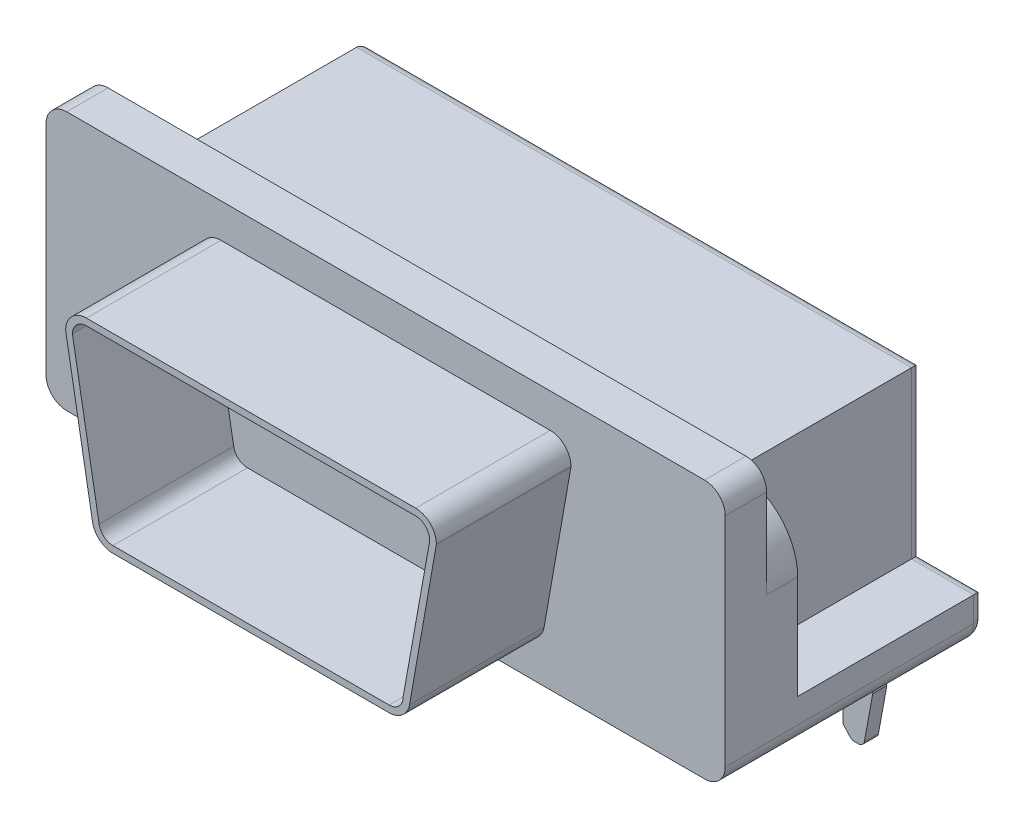
SolidWorks part; units mm, degrees
ref_plane "Front Plane" through (0, 0, 0) normal (0, 0, 1) x (1, 0, 0)
ref_plane "Top Plane" through (0, 0, 0) normal (0, 1, 0) x (1, 0, 0)
ref_plane "Right Plane" through (0, 0, 0) normal (1, 0, 0) x (0, 0, -1)
sketch "Sketch1" plane through (0, 0, 0) normal (0, 1, 0) x (1, 0, 0)
  line L0 (-9.7129, 0) -> (15.2771, 0) construction
  line L13 (-6.925, 1.42) -> (3.5677, 1.42) construction
  line L14 (-5.54, -1.42) -> (3.3918, -1.42) construction
  line L15 (1.045, -1.76) -> (1.045, -1.08)
  line L16 (3.5677, 1.42) -> (3.5677, -3.2608) construction
  line L17 (-5.54, -1.42) -> (-5.54, 1.42) construction
  line L18 (0, 0) -> (0, 1.42) construction
  line L19 (0, 1.42) -> (0, -1.42) construction
  line L20 (-2.77, -1.42) -> (-2.77, 1.42) construction
  line L21 (-1.725, -1.76) -> (-1.045, -1.76)
  line L26 (-1.725, -1.76) -> (-1.725, -1.08)
  line L27 (-1.725, -1.08) -> (-1.045, -1.08)
  line L28 (-5.88, 1.76) -> (-5.2, 1.76)
  line L29 (-5.88, 1.76) -> (-5.88, 1.08)
  line L30 (-5.88, 1.08) -> (-5.2, 1.08)
  line L31 (-5.2, 1.76) -> (-5.2, 1.08)
  line L32 (-5.88, 1.76) -> (-5.2, 1.08) construction
  line L33 (-5.88, 1.08) -> (-5.2, 1.76) construction
  line L34 (-3.11, 1.76) -> (-2.43, 1.76)
  line L35 (-3.11, 1.76) -> (-3.11, 1.08)
  line L36 (-3.11, 1.08) -> (-2.43, 1.08)
  line L37 (-2.43, 1.76) -> (-2.43, 1.08)
  line L38 (-3.11, 1.76) -> (-2.43, 1.08) construction
  line L39 (-3.11, 1.08) -> (-2.43, 1.76) construction
  line L44 (-1.045, -1.76) -> (-1.045, -1.08)
  line L45 (-1.725, -1.76) -> (-1.045, -1.08) construction
  line L50 (-1.725, -1.08) -> (-1.045, -1.76) construction
  line L51 (-4.495, -1.76) -> (-3.815, -1.76)
  line L52 (-0.34, 1.76) -> (0.34, 1.76)
  line L53 (-0.34, 1.76) -> (-0.34, 1.08)
  line L54 (-0.34, 1.08) -> (0.34, 1.08)
  line L55 (0.34, 1.76) -> (0.34, 1.08)
  line L56 (-0.34, 1.76) -> (0.34, 1.08) construction
  line L57 (-0.34, 1.08) -> (0.34, 1.76) construction
  line L62 (-4.495, -1.76) -> (-4.495, -1.08)
  line L63 (-4.495, -1.08) -> (-3.815, -1.08)
  line L64 (-3.815, -1.76) -> (-3.815, -1.08)
  line L65 (-4.495, -1.76) -> (-3.815, -1.08) construction
  line L66 (-4.495, -1.08) -> (-3.815, -1.76) construction
  line L67 (1.725, -1.08) -> (1.045, -1.08)
  line L68 (1.725, -1.76) -> (1.725, -1.08)
  line L69 (1.725, -1.76) -> (1.045, -1.76)
  line L70 (4.495, -1.76) -> (4.495, -1.08)
  line L71 (4.495, -1.76) -> (3.815, -1.76)
  line L72 (3.815, -1.76) -> (3.815, -1.08)
  line L73 (4.495, -1.08) -> (3.815, -1.08)
  line L74 (5.88, 1.76) -> (5.88, 1.08)
  line L75 (5.88, 1.76) -> (5.2, 1.76)
  line L76 (5.2, 1.76) -> (5.2, 1.08)
  line L77 (5.88, 1.08) -> (5.2, 1.08)
  line L78 (3.11, 1.08) -> (2.43, 1.08)
  line L79 (3.11, 1.76) -> (3.11, 1.08)
  line L80 (2.43, 1.76) -> (2.43, 1.08)
  line L81 (3.11, 1.76) -> (2.43, 1.76)
  point P6 (-1.385, -1.42)
  point P23 (-4.155, -1.42)
  dimension "D1" = 2.84
  dimension "D2" = 1.42
  dimension "D3" = 1.385
  dimension "D4" = 2.77
  dimension "D5" = 2.77
  dimension "D6" = 1.385
  dimension "D7" = 0.68
extrude "Boss-Extrude1" add sketch "Sketch1" against normal blind 3.2
sketch "Sketch2" plane through (0, 0, 0) normal (0, 1, 0) x (1, 0, 0)
  line L0 (-5.88, 1.08) -> (-5.2, 1.76) construction
  line L1 (-16.4, -9.52) -> (16.4, -9.52)
  line L2 (-16.4, -9.52) -> (-16.4, 2.98)
  line L3 (-16.4, 2.98) -> (16.4, 2.98)
  line L4 (16.4, -9.52) -> (16.4, 2.98)
  line L5 (-5.2, 1.76) -> (-5.88, 1.76) construction
  line L6 (-5.88, 1.76) -> (-5.179, 1.059) construction
  line L7 (-5.179, 1.059) -> (-5.54, 1.42) construction
  line L8 (0, 0) -> (-7.3423, 0) construction
  line L9 (-4.495, -1.76) -> (-3.815, -1.08) construction
  line L10 (-4.495, -1.08) -> (-3.815, -1.76) construction
  dimension "D1" = 10.94
  dimension "D2" = 12.5
  dimension "D3" = 32.8
  dimension "D4" = 16.4
extrude "Boss-Extrude2" add sketch "Sketch2" along normal blind 12.5
fillet "Fillet1" radius 1 4 edges at (16.4, 12.5, 3.27) (16.4, 0, 3.27) (-16.4, 0, 3.27) (-16.4, 12.5, 3.27)
sketch "Sketch3" plane through (16.4, 0, 0) normal (1, 0, 0) x (0, 0, -1)
  line L1 (2.98, 12.5) -> (-7.52, 12.5)
  line L2 (2.98, 12.5) -> (2.98, 10.2)
  line L3 (2.98, 10.2) -> (-7.52, 10.2)
  line L4 (-7.52, 12.5) -> (-7.52, 10.2)
  dimension "D1" = 2.3
  dimension "D2" = 10.5
extrude "Cut-Extrude1" cut sketch "Sketch3" against normal through all
sketch "Sketch4" plane through (0, 0, 0) normal (0, -1, 0) x (1, 0, 0)
  line L0 (0, 0) -> (-12.495, 0) construction
  line L1 (0, 0) -> (0, 5.4076) construction
  line L2 (-14.345, 0.34) -> (-10.645, 0.34)
  line L3 (-14.345, 0.34) -> (-14.345, -0.34)
  line L4 (-14.345, -0.34) -> (-10.645, -0.34)
  line L5 (-10.645, 0.34) -> (-10.645, -0.34)
  line L6 (-14.345, 0.34) -> (-10.645, -0.34) construction
  line L7 (-14.345, -0.34) -> (-10.645, 0.34) construction
  line L8 (10.645, 0.34) -> (10.645, -0.34)
  line L9 (14.345, -0.34) -> (10.645, -0.34)
  line L10 (14.345, 0.34) -> (14.345, -0.34)
  line L11 (14.345, 0.34) -> (10.645, 0.34)
  dimension "D1" = 12.495
  dimension "D2" = 0.68
  dimension "D3" = 3.7
extrude "Boss-Extrude3" add sketch "Sketch4" along normal blind 4
sketch "Sketch6" plane through (0, 0, 0.34) normal (0, 0, 1) x (1, 0, 0)
  line L0 (-14.345, 0) -> (-10.645, -4) construction
  line L2 (-10.645, 0) -> (-14.345, -4) construction
  line L3 (-12.9071, 0) -> (-12.9071, -3.5332) construction
  line L4 (-10.645, 0) -> (-14.345, 0) construction
  line L5 (-12.9071, -3.5332) -> (-13.3389, -4) construction
  line L6 (-10.645, -4) -> (-14.345, -4) construction
  line L8 (-13.8964, -4) -> (-14.345, -1.5508) construction
  line L9 (-14.345, -4) -> (-14.345, 0) construction
  line L10 (-14.345, -1.5508) -> (-13.8133, -0.7806) construction
  line L11 (-13.8133, -0.7806) -> (-13.8133, 0) construction
  line L12 (-15.4, 0) -> (15.4, 0) construction
  line L15 (-14.345, -1.5508) -> (-13.8133, -0.7806)
  line L16 (-13.8133, -0.7806) -> (-13.8133, 0)
  line L20 (-12.495, -2) -> (-12.495, 0) construction
  line L22 (-14.8273, 0) -> (-14.8273, -4)
  line L23 (-14.8273, -4) -> (-13.8964, -4)
  line L24 (-13.8964, -4) -> (-14.345, -1.5508)
  line L25 (-14.345, 0) -> (-14.8273, 0)
  line L26 (-12.9071, 0) -> (-12.0829, 0)
  line L40 (-13.8133, 0) -> (-14.345, 0)
  line L42 (-12.9071, 0) -> (-12.9071, -3.5332)
  line L43 (-12.9071, -3.5332) -> (-13.3389, -4)
  line L44 (-12.495, -2) -> (-12.495, -4) construction
  line L45 (-13.3389, -4) -> (-11.6511, -4)
  line L46 (-11.1767, -0.7806) -> (-11.1767, 0) construction
  line L47 (-10.645, -1.5508) -> (-11.1767, -0.7806) construction
  line L48 (-11.0936, -4) -> (-10.645, -1.5508) construction
  line L49 (-12.0829, -3.5332) -> (-11.6511, -4) construction
  line L50 (-12.0829, 0) -> (-12.0829, -3.5332) construction
  line L51 (-12.0829, -3.5332) -> (-11.6511, -4)
  line L52 (-12.0829, 0) -> (-12.0829, -3.5332)
  line L53 (-11.1767, 0) -> (-10.645, 0)
  line L54 (-10.645, 0) -> (-10.1627, 0)
  line L55 (-11.0936, -4) -> (-10.645, -1.5508)
  line L56 (-10.1627, -4) -> (-11.0936, -4)
  line L57 (-10.1627, 0) -> (-10.1627, -4)
  line L58 (-11.1767, -0.7806) -> (-11.1767, 0)
  line L59 (-10.645, -1.5508) -> (-11.1767, -0.7806)
  line L60 (0, 0) -> (0, -4) construction
  line L61 (12.0829, 0) -> (12.0829, -3.5332) construction
  line L62 (12.0829, -3.5332) -> (11.6511, -4) construction
  line L63 (11.0936, -4) -> (10.645, -1.5508) construction
  line L64 (10.645, -1.5508) -> (11.1767, -0.7806) construction
  line L65 (11.1767, -0.7806) -> (11.1767, 0) construction
  line L66 (12.495, -2) -> (12.495, -4) construction
  line L67 (12.495, -2) -> (12.495, 0) construction
  line L68 (13.8133, -0.7806) -> (13.8133, 0) construction
  line L69 (14.345, -1.5508) -> (13.8133, -0.7806) construction
  line L70 (13.8964, -4) -> (14.345, -1.5508) construction
  line L71 (12.9071, -3.5332) -> (13.3389, -4) construction
  line L72 (12.9071, 0) -> (12.9071, -3.5332) construction
  line L73 (10.645, 0) -> (14.345, -4) construction
  line L74 (14.345, 0) -> (10.645, -4) construction
  line L75 (10.645, -1.5508) -> (11.1767, -0.7806)
  line L76 (11.1767, -0.7806) -> (11.1767, 0)
  line L77 (10.1627, 0) -> (10.1627, -4)
  line L78 (10.1627, -4) -> (11.0936, -4)
  line L79 (11.0936, -4) -> (10.645, -1.5508)
  line L80 (10.645, 0) -> (10.1627, 0)
  line L81 (11.1767, 0) -> (10.645, 0)
  line L82 (12.0829, 0) -> (12.0829, -3.5332)
  line L83 (12.0829, -3.5332) -> (11.6511, -4)
  line L84 (13.3389, -4) -> (11.6511, -4)
  line L85 (12.9071, -3.5332) -> (13.3389, -4)
  line L86 (12.9071, 0) -> (12.9071, -3.5332)
  line L87 (13.8133, 0) -> (14.345, 0)
  line L88 (12.9071, 0) -> (12.0829, 0)
  line L89 (14.345, 0) -> (14.8273, 0)
  line L90 (13.8964, -4) -> (14.345, -1.5508)
  line L91 (14.8273, -4) -> (13.8964, -4)
  line L92 (14.8273, 0) -> (14.8273, -4)
  line L93 (13.8133, -0.7806) -> (13.8133, 0)
  line L94 (14.345, -1.5508) -> (13.8133, -0.7806)
extrude "Cut-Extrude5" cut sketch "Sketch6" against normal through all
fillet "Fillet2" radius 0.3 8 edges at (13.8964, -4, 0) (13.3389, -4, 0) (11.6511, -4, 0) (11.0936, -4, 0) (-11.0936, -4, 0) (-11.6511, -4, 0) (-13.3389, -4, 0) (-13.8964, -4, 0)
sketch "Sketch7" plane through (0, 0, 9.52) normal (0, 0, 1) x (1, 0, 0)
  line L0 (0, 0) -> (0, 12.5) construction
  line L1 (-15.4, 12.5) -> (15.4, 12.5) construction
  line L2 (0, 12.5) -> (0, 6.25) construction
  line L3 (0, 6.25) -> (-16.4, 6.25) construction
  line L4 (-16.4, 11.5) -> (-16.4, 1) construction
  line L5 (0, 6.25) -> (16.4, 6.25) construction
  line L6 (16.4, 11.5) -> (16.4, 1) construction
  line L7 (-8.95, 10.85) -> (8.95, 10.85)
  line L8 (-8.95, 10.85) -> (8.95, 10.85) construction
  line L9 (-8.95, 10.85) -> (-8.95, 1.65) construction
  line L10 (-8.95, 1.65) -> (8.95, 1.65) construction
  line L11 (8.95, 10.85) -> (8.95, 1.65) construction
  line L12 (-8.95, 10.85) -> (8.95, 1.65) construction
  line L13 (-8.95, 1.65) -> (8.95, 10.85) construction
  line L14 (8.95, 10.85) -> (8.95, 9.8239)
  line L15 (8.95, 9.8239) -> (7.5087, 1.65)
  line L16 (7.5087, 1.65) -> (-7.5087, 1.65)
  line L17 (-7.5087, 1.65) -> (-8.95, 9.8239)
  line L18 (-8.95, 9.8239) -> (-8.95, 10.85)
  dimension "D1" = 17.9
  dimension "D2" = 9.2
  dimension "D3" = 8.3
  dimension "D4" = 100
  dimension "D5" = 100
  dimension "D6" = 8.3
extrude "Boss-Extrude4" add sketch "Sketch7" along normal blind 6.5
fillet "Fillet3" radius 1 4 edges at (-7.5087, 1.65, 12.77) (7.5087, 1.65, 12.77) (-8.95, 10.85, 12.77) (8.95, 10.85, 12.77)
sketch "Sketch10" plane through (0, 0, 16.02) normal (0, 0, 1) x (1, 0, 0)
  line L0 (-8.625, 9.85) -> (-7.3357, 2.5403)
  line L1 (7.95, 10.525) -> (-7.95, 10.525)
  line L7 (-6.6696, 1.975) -> (6.6696, 1.975)
  line L8 (7.3446, 2.65) -> (8.6213, 9.7794)
  arc A4 (-7.95, 10.525) -> (-8.625, 9.85) centre (-7.95, 9.85) ccw
  arc A5 (8.6213, 9.7794) -> (7.95, 10.525) centre (7.95, 9.85) ccw
  arc A6 (6.6696, 1.975) -> (7.3446, 2.65) centre (6.6696, 2.65) ccw
  arc A7 (-7.3357, 2.5403) -> (-6.6696, 1.975) centre (-6.6696, 2.65) ccw
extrude "Cut-Extrude6" cut sketch "Sketch10" against normal blind 6.5
fillet "Fillet4" radius 3 2 edges at (16.4, 10.2, 2.27) (-16.4, 10.2, 2.27)
sketch "Sketch12" plane through (0, 10.2, 0) normal (0, 1, 0) x (1, 0, 0)
  line L0 (-13.4, 2.98) -> (-13.4, -7.52) construction
  line L1 (-16.4, 2.98) -> (-13.4, 2.98)
  line L2 (-16.4, 2.98) -> (-16.4, -6.02)
  line L3 (-16.4, -6.02) -> (-13.4, -6.02)
  line L4 (-13.4, 2.98) -> (-13.4, -6.02)
  line L5 (0, 0) -> (0, -3.0225) construction
  line L6 (13.4, 2.98) -> (13.4, -6.02)
  line L7 (16.4, -6.02) -> (13.4, -6.02)
  line L8 (16.4, 2.98) -> (16.4, -6.02)
  line L9 (16.4, 2.98) -> (13.4, 2.98)
  dimension "D1" = 9
extrude "Cut-Extrude7" cut sketch "Sketch12" against normal blind 8
fillet "Fillet5" radius 0.5 10 edges at (-16.4, 1.6, -2.98) (-16.1071, 0.2929, -2.98) (0, 0, -2.98) (16.1071, 0.2929, -2.98) (16.4, 1.6, -2.98) (14.9, 2.2, -2.98) (13.4, 6.2, -2.98) (0, 10.2, -2.98) (-13.4, 6.2, -2.98) (-14.9, 2.2, -2.98)
